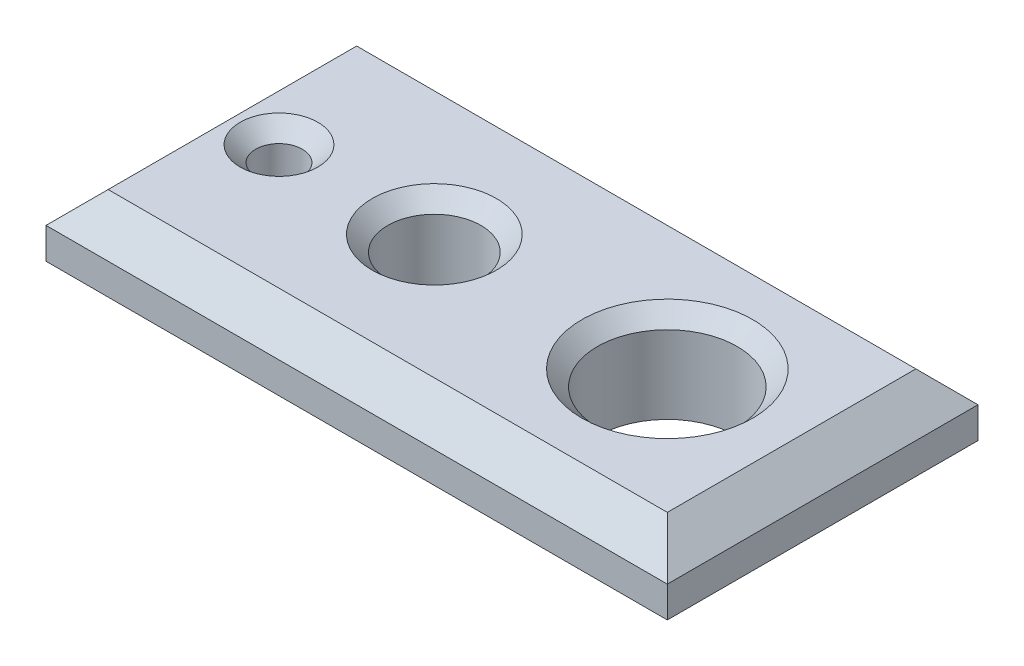
SolidWorks part; units mm, degrees
ref_plane "Front Plane" through (0, 0, 0) normal (0, 0, 1) x (1, 0, 0)
ref_plane "Top Plane" through (0, 0, 0) normal (0, 1, 0) x (1, 0, 0)
ref_plane "Right Plane" through (0, 0, 0) normal (1, 0, 0) x (0, 0, -1)
sketch "Sketch1" plane through (0, 0, 0) normal (0, 1, 0) x (1, 0, 0)
  line L1 (-100, 50) -> (100, 50)
  line L2 (-100, 50) -> (-100, -50)
  line L3 (-100, -50) -> (100, -50)
  line L4 (100, 50) -> (100, -50)
  line L5 (0, -50) -> (0, 50) construction
  line L6 (-100, 0) -> (100, 0) construction
  point P0 (0, 0)
  dimension "D1" = 200
  dimension "D2" = 100
extrude "Boss-Extrude1" add sketch "Sketch1" along normal blind 30
chamfer "Chamfer1" distance 10 angle 45 8 edges at (0, 0, 50) (-100, 0, 0) (0, 0, -50) (100, 0, 0) (100, 30, 0) (0, 30, -50) (-100, 30, 0) (0, 30, 50)
sketch "Sketch2" plane through (0, 30, 0) normal (0, 1, 0) x (1, 0, 0)
  line L0 (-100, -50) -> (-100, 50) construction
  circle A0 centre (-75, 0) radius 7.5
  circle A1 centre (-25, 0) radius 15
  circle A2 centre (50, 0) radius 22.5
  dimension "D2" = 15
  dimension "D4" = 30
  dimension "D6" = 45
  dimension "D1" = 25
  dimension "D3" = 50
  dimension "D5" = 75
extrude "Cut-Extrude1" cut sketch "Sketch2" against normal through all
chamfer "Chamfer3" distance 5 angle 45 3 edges at (-75, 30, 7.5) (-25, 30, 15) (50, 30, 22.5)
